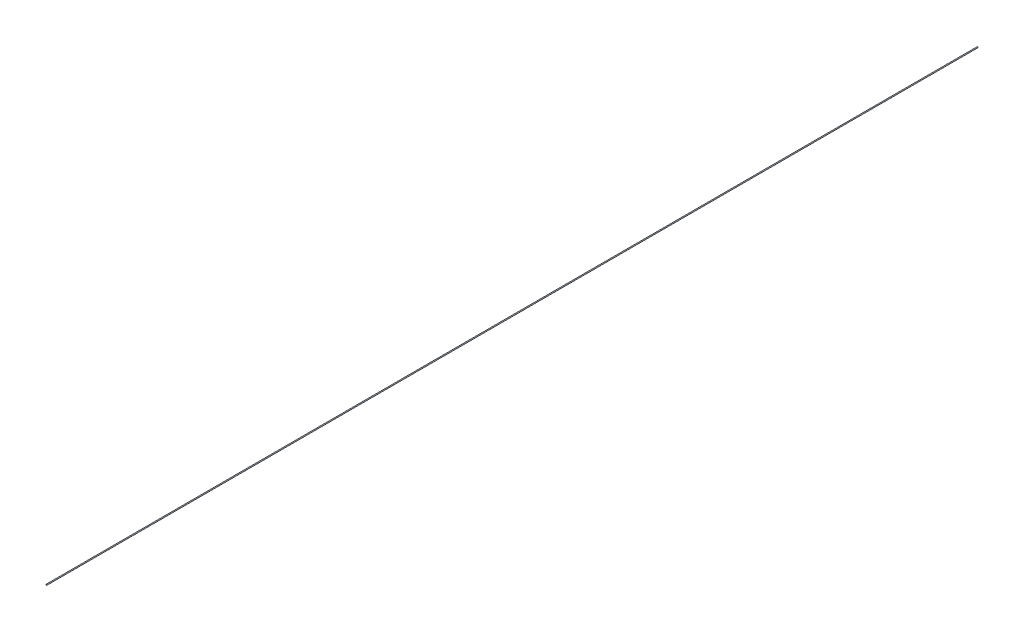
SolidWorks part; units mm, degrees
ref_plane "Front Plane" through (0, 0, 0) normal (0, 0, 1) x (1, 0, 0)
ref_plane "Top Plane" through (0, 0, 0) normal (0, 1, 0) x (1, 0, 0)
ref_plane "Right Plane" through (0, 0, 0) normal (1, 0, 0) x (0, 0, -1)
sketch "Sketch3" plane through (0, 0, 0) normal (0, 0, 1) x (1, 0, 0)
  circle A0 centre (0, 0) radius 0.5
  dimension "D1" = 1
extrude "Boss-Extrude1" add sketch "Sketch3" along normal mid plane 1016
fillet "Fillet1" radius 0.4 2 edges at (0.5, 0, 508) (0.5, 0, -508)
equation "\"40x25.4\"=500"
